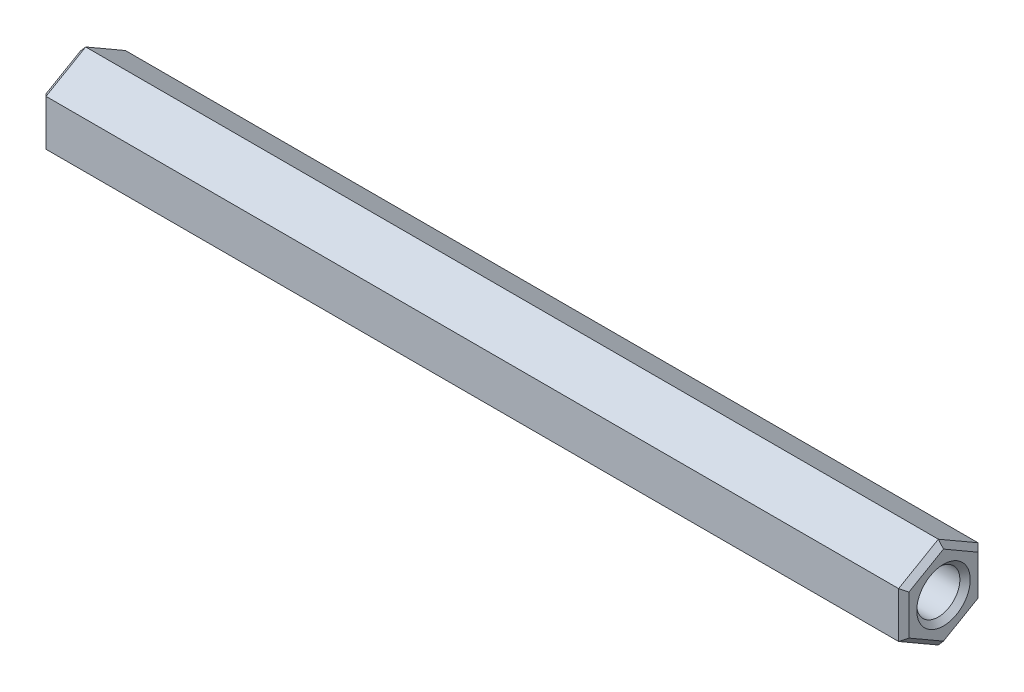
SolidWorks part; units mm, degrees
material "黄铜"
ref_plane "前视基准面" through (0, 0, 0) normal (1, 0, 0) x (0, 1, 0)
ref_plane "上视基准面" through (0, 0, 0) normal (0, 0, 1) x (0, 1, 0)
ref_plane "右视基准面" through (0, 0, 0) normal (0, 1, 0) x (-1, 0, 0)
other "Configuration Table"
sketch "草图1" plane through (0, 0, 0) normal (1, 0, 0) x (0, 1, 0)
  line L0 (0, 0) -> (2.6558, 0) construction
  line L1 (2.6558, 0) -> (1.3279, 2.3)
  line L2 (1.3279, 2.3) -> (-1.3279, 2.3)
  line L3 (-1.3279, 2.3) -> (-2.6558, 0)
  line L4 (-2.6558, 0) -> (-1.3279, -2.3)
  line L5 (-1.3279, -2.3) -> (1.3279, -2.3)
  line L6 (1.3279, -2.3) -> (2.6558, 0)
  circle A0 centre (0, 0) radius 1.25
  circle A1 centre (0, 0) radius 2.3 construction
  dimension "D1" = 2.5
  dimension "D2" = 4.6
extrude "凸台-拉伸1" add sketch "草图1" along normal blind 50
chamfer "倒角1" distance 0.3 angle 45 14 edges at (0, 0, -1.25) (0, 1.9919, 1.15) (0, 0, 2.3) (0, -1.9919, 1.15) (0, -1.9919, -1.15) (0, 0, -2.3) (0, 1.9919, -1.15) (50, 0, -1.25) (50, 0, -2.3) (50, -1.9919, -1.15) (50, -1.9919, 1.15) (50, 0, 2.3) (50, 1.9919, 1.15) (50, 1.9919, -1.15)
